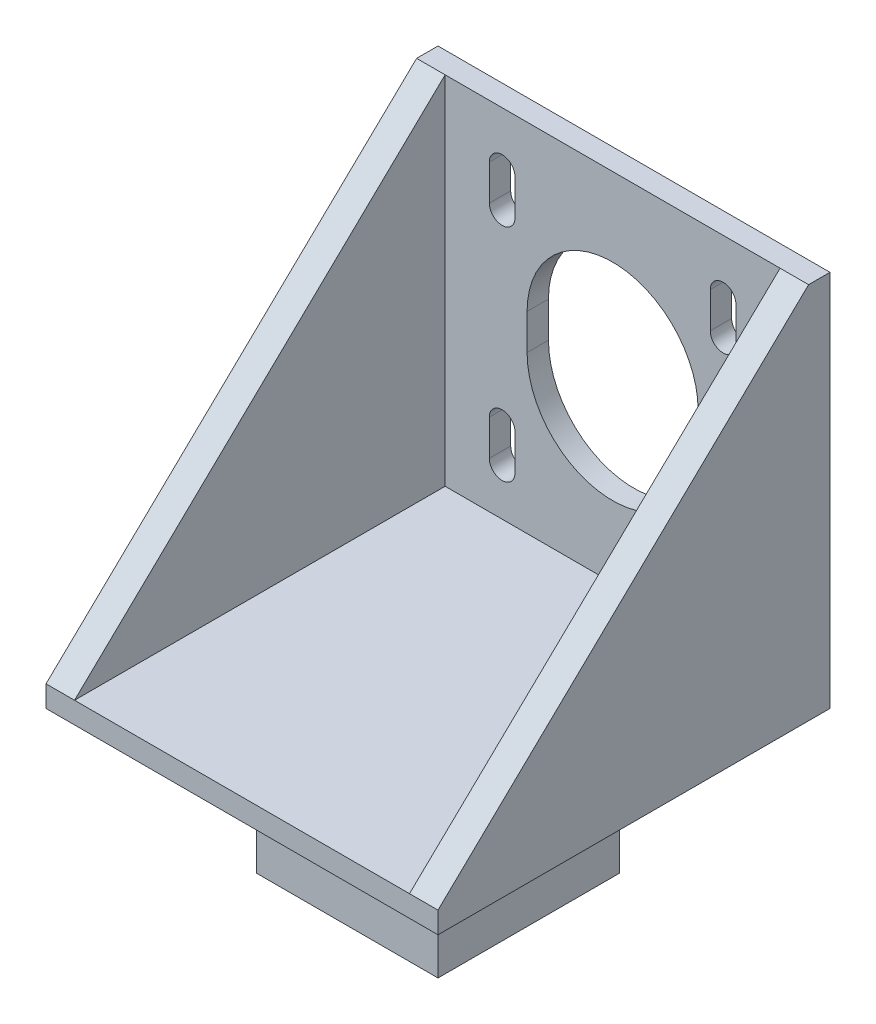
SolidWorks part; units mm, degrees
ref_plane "Front Plane" through (0, 0, 0) normal (0, 0, 1) x (1, 0, 0)
ref_plane "Top Plane" through (0, 0, 0) normal (0, 1, 0) x (1, 0, 0)
ref_plane "Right Plane" through (0, 0, 0) normal (1, 0, 0) x (0, 0, -1)
sketch "Sketch1" plane through (0, 0, 0) normal (0, 1, 0) x (1, 0, 0)
  line L1 (-9.75, -9.75) -> (9.75, -9.75)
  line L2 (-9.75, -9.75) -> (-9.75, 9.75)
  line L3 (-9.75, 9.75) -> (9.75, 9.75)
  line L4 (9.75, -9.75) -> (9.75, 9.75)
  line L5 (-9.75, -9.75) -> (9.75, 9.75) construction
  line L6 (-9.75, 9.75) -> (9.75, -9.75) construction
  line L7 (-12.75, -12.75) -> (12.75, -12.75)
  line L8 (-12.75, -12.75) -> (-12.75, 12.75)
  line L9 (-12.75, 12.75) -> (12.75, 12.75)
  line L10 (12.75, -12.75) -> (12.75, 12.75)
  line L11 (-12.75, -12.75) -> (12.75, 12.75) construction
  line L12 (-12.75, 12.75) -> (12.75, -12.75) construction
  point P0 (0, 0)
  point P6 (0, 0)
  dimension "D1" = 19.5
  dimension "D2" = 3
extrude "Boss-Extrude1" add sketch "Sketch1" against normal blind 20
sketch "Sketch2" plane through (0, 0, 0) normal (0, 1, 0) x (1, 0, 0)
  line L1 (-27.5, -27.5) -> (27.5, -27.5)
  line L2 (-27.5, -27.5) -> (-27.5, 27.5)
  line L3 (-27.5, 27.5) -> (27.5, 27.5)
  line L4 (27.5, -27.5) -> (27.5, 27.5)
  line L5 (-27.5, -27.5) -> (27.5, 27.5) construction
  line L6 (-27.5, 27.5) -> (27.5, -27.5) construction
  point P0 (0, 0)
  dimension "D1" = 55
extrude "Boss-Extrude2" add sketch "Sketch2" along normal blind 3
sketch "Sketch3" plane through (0, 3, 0) normal (0, 1, 0) x (1, 0, 0)
  line L0 (27.5, -27.5) -> (27.5, 27.5) construction
  line L1 (-27.5, 27.5) -> (27.5, 27.5)
  line L2 (-27.5, 27.5) -> (-27.5, 24.5)
  line L3 (-27.5, 24.5) -> (27.5, 24.5)
  line L4 (27.5, 27.5) -> (27.5, 24.5)
  dimension "D1" = 3
extrude "Boss-Extrude3" add sketch "Sketch3" along normal blind 50
sketch "Sketch4" plane through (-27.5, 0, 0) normal (-1, 0, 0) x (0, 0, 1)
  line L0 (-24.5, 3) -> (27.5, 3) construction
  line L1 (-24.5, 53) -> (-24.5, 3) construction
  line L2 (-24.5, 3) -> (27.5, 3)
  line L3 (-24.5, 53) -> (-24.5, 3)
  line L4 (-24.5, 53) -> (27.5, 3)
extrude "Boss-Extrude4" add sketch "Sketch4" against normal blind 4
mirror "Mirror1" about plane through (0, 0, 0) normal (1, 0, 0) of "Boss-Extrude4"
sketch "Sketch5" plane through (0, 0, -24.5) normal (0, 0, 1) x (1, 0, 0)
  line L0 (-23.5, 3) -> (23.5, 3) construction
  line L1 (-15.5, 9.5) -> (15.5, 9.5) construction
  line L2 (-15.5, 9.5) -> (-15.5, 40.5) construction
  line L3 (-15.5, 40.5) -> (15.5, 40.5) construction
  line L4 (15.5, 9.5) -> (15.5, 40.5) construction
  line L5 (-15.5, 9.5) -> (15.5, 40.5) construction
  line L6 (-15.5, 40.5) -> (15.5, 9.5) construction
  line L7 (-15.5, 9.5) -> (-15.5, 14.5) construction
  line L8 (-17.3, 9.5) -> (-17.3, 14.5)
  line L9 (-13.7, 9.5) -> (-13.7, 14.5)
  line L10 (15.5, 9.5) -> (15.5, 14.5) construction
  line L11 (13.7, 9.5) -> (13.7, 14.5)
  line L12 (17.3, 9.5) -> (17.3, 14.5)
  line L13 (15.5, 40.5) -> (15.5, 45.5) construction
  line L14 (13.7, 40.5) -> (13.7, 45.5)
  line L15 (17.3, 40.5) -> (17.3, 45.5)
  line L16 (-15.5, 40.5) -> (-15.5, 45.5) construction
  line L17 (-17.3, 40.5) -> (-17.3, 45.5)
  line L18 (-13.7, 40.5) -> (-13.7, 45.5)
  line L19 (0, 25) -> (0, 30) construction
  line L20 (-12, 25) -> (-12, 30)
  line L21 (12, 25) -> (12, 30)
  arc A0 (-17.3, 9.5) -> (-13.7, 9.5) centre (-15.5, 9.5) ccw
  arc A1 (-13.7, 14.5) -> (-17.3, 14.5) centre (-15.5, 14.5) ccw
  arc A2 (13.7, 9.5) -> (17.3, 9.5) centre (15.5, 9.5) ccw
  arc A3 (17.3, 14.5) -> (13.7, 14.5) centre (15.5, 14.5) ccw
  arc A4 (13.7, 40.5) -> (17.3, 40.5) centre (15.5, 40.5) ccw
  arc A5 (17.3, 45.5) -> (13.7, 45.5) centre (15.5, 45.5) ccw
  arc A6 (-17.3, 40.5) -> (-13.7, 40.5) centre (-15.5, 40.5) ccw
  arc A7 (-13.7, 45.5) -> (-17.3, 45.5) centre (-15.5, 45.5) ccw
  arc A8 (-12, 25) -> (12, 25) centre (0, 25) ccw
  arc A9 (12, 30) -> (-12, 30) centre (0, 30) ccw
  point P0 (0, 25)
  point P5 (-15.5, 12)
  point P14 (15.5, 12)
  point P20 (15.5, 43)
  point P26 (-15.5, 43)
  point P32 (0, 27.5)
  dimension "D4" = 3.6
  dimension "D5" = 12
  dimension "D1" = 31
  dimension "D2" = 22
  dimension "D3" = 5
extrude "Cut-Extrude1" cut sketch "Sketch5" against normal through all
